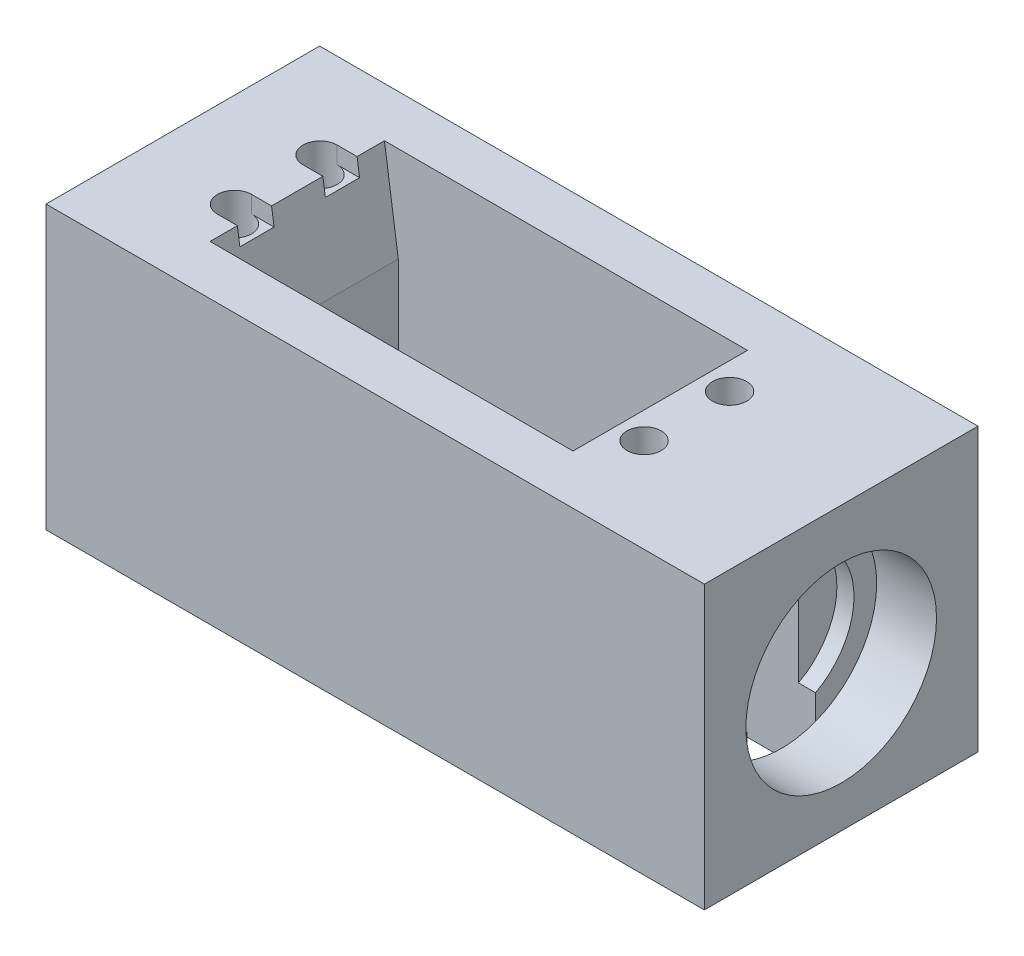
SolidWorks part; units mm, degrees
ref_plane "Front Plane" through (0, 0, 0) normal (0, 0, 1) x (1, 0, 0)
ref_plane "Top Plane" through (0, 0, 0) normal (0, 1, 0) x (1, 0, 0)
ref_plane "Right Plane" through (0, 0, 0) normal (1, 0, 0) x (0, 0, -1)
sketch "Sketch2" plane through (0, 0, 0) normal (0, 1, 0) x (1, 0, 0)
  line L1 (0, 0) -> (40, 0) construction
  line L2 (0, 0) -> (0, 20) construction
  line L3 (0, 20) -> (40, 20) construction
  line L4 (40, 0) -> (40, 20) construction
  line L5 (0, 20) -> (-8, 20)
  line L6 (0, 20) -> (0, 0)
  line L7 (0, 0) -> (-8, 0)
  line L8 (-8, 20) -> (-8, 0)
  line L9 (40, 0) -> (48, 0)
  line L10 (40, 0) -> (40, 20)
  line L11 (40, 20) -> (48, 20)
  line L12 (48, 0) -> (48, 20)
  line L13 (-8, 0) -> (48, 0)
  line L14 (-8, 0) -> (-8, -6)
  line L15 (-8, -6) -> (48, -6)
  line L16 (48, 0) -> (48, -6)
  line L17 (0, 0) -> (40, 0) construction
  line L18 (0, 0) -> (0, 20) construction
  line L19 (0, 20) -> (40, 20) construction
  line L20 (40, 0) -> (40, 20) construction
  line L21 (0, 0) -> (40, 20) construction
  line L22 (0, 20) -> (40, 0) construction
  point P8 (20, 10)
  dimension "D1" = 8
  dimension "D2" = 20
  dimension "D3" = 40
  dimension "D7" = 6
extrude "Boss-Extrude1" add sketch "Sketch2" along normal blind 5
sketch "Sketch6" plane through (0, 0, 0) normal (0, -1, 0) x (1, 0, 0)
  line L0 (40, -10) -> (0, -10) construction
  line L1 (-3.95, -5) -> (43.95, -5) construction
  line L2 (-3.95, -5) -> (-3.95, -15) construction
  line L3 (-3.95, -15) -> (43.95, -15) construction
  line L4 (43.95, -5) -> (43.95, -15) construction
  line L5 (40, 0) -> (40, -20) construction
  line L6 (0, -20) -> (0, 0) construction
  line L7 (20, -10) -> (20, -15) construction
  line L8 (20, -10) -> (20, -5) construction
  circle A0 centre (43.95, -5) radius 2
  circle A1 centre (43.95, -15) radius 2
  circle A2 centre (-3.95, -5) radius 2
  circle A3 centre (-3.95, -15) radius 2
  dimension "D3" = 4
  dimension "D1" = 10
  dimension "D2" = 47.9
extrude "Cut-Extrude3" cut sketch "Sketch6" against normal through all contours A2
sketch "Sketch7" plane through (0, 0, 0) normal (0, -1, 0) x (1, 0, 0)
  line L0 (-8, -20) -> (-8, 6) construction
  line L1 (48, 6) -> (-8, 6)
  line L2 (48, 6) -> (48, 0)
  line L3 (48, 0) -> (-8, 0)
  line L4 (-8, 6) -> (-8, 0)
  line L5 (0, 0) -> (40, 0) construction
extrude "Boss-Extrude2" add sketch "Sketch7" along normal blind 28
sketch "Sketch8" plane through (48, 0, 0) normal (1, 0, 0) x (0, 0, -1)
  line L1 (-6, -28) -> (20, -28)
  line L2 (-6, -28) -> (-6, 5)
  line L3 (-6, 5) -> (20, 5)
  line L4 (20, -28) -> (20, 5)
  line M5 (0, 0) -> (20, 0)
  line M6 (20, 0) -> (20, 5)
  line M7 (20, 5) -> (-6, 5)
  line M8 (-6, 5) -> (-6, -28)
  line M9 (-6, -28) -> (0, -28)
  line M10 (0, -28) -> (0, 0)
sketch "Sketch9" plane through (-8, 0, 0) normal (-1, 0, 0) x (0, 0, 1)
  line L1 (-20, 5) -> (6, 5)
  line L2 (-20, 5) -> (-20, -28)
  line L3 (-20, -28) -> (6, -28)
  line L4 (6, 5) -> (6, -28)
  line M1 (-20, 0) -> (0, 0)
  line M2 (0, 0) -> (0, -28)
  line M3 (0, -28) -> (6, -28)
  line M4 (6, -28) -> (6, 5)
  line M5 (6, 5) -> (-20, 5)
  line M6 (-20, 5) -> (-20, 0)
extrude "Boss-Extrude3" add sketch "Sketch9" along normal blind 2 contours M6 M1 M2 M3 M4 M5 | L2 L3 M2 M1
extrude "Boss-Extrude4" add sketch "Sketch8" along normal blind 2 contours L1 L4 M5 M10 | M10 M5 M6 M7 M8 M9
sketch "Sketch10" plane through (0, 0, 0) normal (0, -1, 0) x (1, 0, 0)
  line L4 (0, 0) -> (-8, 0)
  line L5 (-8, 0) -> (-8, -20)
  line L6 (-8, -20) -> (0, -20)
  line L7 (0, -20) -> (0, 0)
  line L8 (0, 0) -> (-8, 0)
  line L9 (-8, 0) -> (-8, -20)
  line L10 (-8, -20) -> (0, -20)
  line L11 (0, -20) -> (0, 0)
  circle A0 centre (-3.95, -5) radius 2 construction
  circle A1 centre (-3.95, -15) radius 2 construction
  circle A2 centre (-3.95, -5) radius 2
  circle A3 centre (-3.95, -15) radius 2
  dimension "D1" = 0
extrude "Boss-Extrude5" add sketch "Sketch10" along normal up to surface (28 mm away) up to face at (20, -28, -8.5)
sketch "Sketch12" plane through (0, 0, -20) normal (0, 0, -1) x (-1, 0, 0)
  line L0 (1.6175, 5) -> (0, -6.1672)
  line L1 (0, 5) -> (10, 5) construction
  line L2 (0, 5) -> (0, -28) construction
  line L3 (0, -6.1672) -> (0, 5)
  line L4 (0, 5) -> (1.6175, 5)
  line L5 (-40, 2.5) -> (-40.8379, 5)
  line L6 (-40, 5) -> (-50, 5) construction
  line L7 (-40.8379, 5) -> (-40, 5)
  line L8 (-40, 5) -> (-40, 2.5)
  line L9 (-40, 5) -> (-40, 0) construction
  line M1 (0, 5) -> (0, -28)
  line M4 (10, 5) -> (0, 5)
extrude "Cut-Extrude4" cut sketch "Sketch12" against normal up to surface (20 mm away) contours L8 L7 L5 | L0 M4 M1 up to face at (29.3333, -7.6667, 0)
sketch "Sketch13" plane through (0, 5, 0) normal (0, 1, 0) x (1, 0, 0)
  line L0 (0, 0) -> (0, 20) construction
  line L1 (-3.95, 7) -> (0, 7)
  line L2 (-3.95, 7) -> (-3.95, 3)
  line L3 (-3.95, 3) -> (0, 3)
  line L4 (0, 7) -> (0, 3)
  line L5 (-3.95, 17) -> (0, 17)
  line L6 (-3.95, 17) -> (-3.95, 13)
  line L7 (-3.95, 13) -> (0, 13)
  line L8 (0, 17) -> (0, 13)
  circle A0 centre (-3.95, 15) radius 2 construction
  circle A1 centre (-3.95, 5) radius 2 construction
  circle A2 centre (-3.95, 15) radius 2 construction
  circle A3 centre (-3.95, 5) radius 2 construction
extrude "Cut-Extrude5" cut sketch "Sketch13" against normal blind 2
sketch "Sketch14" plane through (0, 0, -20) normal (0, 0, -1) x (-1, 0, 0)
  line L1 (-50, 5) -> (10, 5)
  line L2 (-50, 5) -> (-50, -28)
  line L3 (-50, -28) -> (10, -28)
  line L4 (10, 5) -> (10, -28)
extrude "Boss-Extrude6" add sketch "Sketch14" along normal blind 6
sketch "Sketch15" plane through (0, -28, 0) normal (0, -1, 0) x (1, 0, 0)
  circle A0 centre (-3.95, -5) radius 2 construction
  circle A1 centre (-3.95, -15) radius 2 construction
  circle A2 centre (-3.95, -5) radius 2
  circle A3 centre (-3.95, -15) radius 2
extrude "Boss-Extrude7" add sketch "Sketch15" against normal blind 20
sketch "Sketch16" plane through (50, 0, 0) normal (1, 0, 0) x (0, 0, -1)
  line L4 (-6, -28) -> (26, -28)
  line L5 (26, -28) -> (26, 5)
  line L6 (26, 5) -> (-6, 5)
  line L7 (-6, 5) -> (-6, -28)
  line L8 (-6, -28) -> (26, -28)
  line L9 (26, -28) -> (26, 5)
  line L10 (26, 5) -> (-6, 5)
  line L11 (-6, 5) -> (-6, -28)
  dimension "D1" = 0
extrude "Boss-Extrude8" add sketch "Sketch16" along normal blind 12
sketch "Sketch20" plane through (-10, 0, 0) normal (-1, 0, 0) x (0, 0, 1)
  line L4 (6, 5) -> (-26, 5)
  line L5 (-26, 5) -> (-26, -28)
  line L6 (-26, -28) -> (6, -28)
  line L7 (6, -28) -> (6, 5)
  line L8 (6, 5) -> (-26, 5)
  line L9 (-26, 5) -> (-26, -28)
  line L10 (-26, -28) -> (6, -28)
  line L11 (6, -28) -> (6, 5)
  dimension "D1" = 0
extrude "Boss-Extrude9" add sketch "Sketch20" along normal blind 5
sketch "Sketch17" plane through (62, 0, 0) normal (1, 0, 0) x (0, 0, -1)
  line L0 (10, -28) -> (10, -12) construction
  line L1 (-6, -28) -> (26, -28) construction
  circle A0 centre (10, -12) radius 11.15
  dimension "D1" = 22.3
  dimension "D2" = 16
extrude "Cut-Extrude6" cut sketch "Sketch17" against normal blind 7
sketch "Sketch19" plane through (-15, 0, 0) normal (-1, 0, 0) x (0, 0, 1)
  circle A0 centre (-10, -12) radius 11.15 construction
  circle A1 centre (-10, -12) radius 11.15
extrude "Cut-Extrude7" cut sketch "Sketch19" against normal blind 7
sketch "Sketch21" plane through (55, 0, 0) normal (1, 0, 0) x (0, 0, -1)
  circle A0 centre (10, -12) radius 8.5
  dimension "D1" = 17
extrude "Cut-Extrude8" cut sketch "Sketch21" against normal blind 2
sketch "Sketch22" plane through (0, -28, 0) normal (0, -1, 0) x (1, 0, 0)
  line L0 (48, -10) -> (51.5, -10) construction
  line L1 (48, 0) -> (48, -20) construction
  line L3 (55, -6) -> (48, -6)
  line L4 (55, -6) -> (55, -14)
  line L5 (55, -14) -> (48, -14)
  line L6 (48, -6) -> (48, -14)
  line L7 (55, -6) -> (48, -14) construction
  line L8 (55, -14) -> (48, -6) construction
  dimension "D1" = 8
  dimension "D2" = 7
extrude "Cut-Extrude10" cut sketch "Sketch22" against normal up to surface (28 mm away) contours L5 L6 L3 L4
sketch "Sketch25" plane through (0, 0, 0) normal (0, -1, 0) x (1, 0, 0)
  line L0 (48, -20) -> (48, -14) construction
  line L1 (40, 0) -> (48, 0)
  line L2 (40, 0) -> (40, -6)
  line L3 (40, -6) -> (48, -6)
  line L4 (48, 0) -> (48, -6)
  line L5 (40, -20) -> (48, -20)
  line L6 (40, -20) -> (40, -14)
  line L7 (40, -14) -> (48, -14)
  line L8 (48, -20) -> (48, -14)
  line L9 (48, -6) -> (48, 0) construction
  line L10 (55, -14) -> (48, -14) construction
extrude "Boss-Extrude10" add sketch "Sketch25" along normal up to surface (28 mm away) up to face at (37.75, -28, -10)
sketch "Sketch26" plane through (0, 5, 0) normal (0, 1, 0) x (1, 0, 0)
  circle A0 centre (43.95, 5) radius 2 construction
  circle A1 centre (43.95, 15) radius 2 construction
  circle A2 centre (43.95, 5) radius 2
  circle A3 centre (43.95, 15) radius 2
extrude "Cut-Extrude11" cut sketch "Sketch26" against normal blind 12
sketch "Sketch27" plane through (-8, 0, 0) normal (-1, 0, 0) x (0, 0, 1)
  arc A0 (-6, -19.5) -> (-6, -4.5) centre (-10, -12) ccw construction
  arc A1 (-14, -4.5) -> (-14, -19.5) centre (-10, -12) ccw construction
  arc A2 (-6, -19.5) -> (-6, -4.5) centre (-10, -12) ccw construction
  arc A3 (-14, -4.5) -> (-14, -19.5) centre (-10, -12) ccw construction
  circle A4 centre (-10, -12) radius 8.5
extrude "Cut-Extrude12" cut sketch "Sketch27" against normal blind 2
sketch "Sketch28" plane through (0, 0, 0) normal (0, 0, -1) x (-1, 0, 0)
  line L6 (-40, 2.5) -> (-40, -28)
  line L7 (-40, -28) -> (0, -28)
  line L8 (0, -28) -> (0, -6.1672)
  line L9 (0, -6.1672) -> (1.6175, 5)
  line L10 (1.6175, 5) -> (-40.8379, 5)
  line L11 (-40.8379, 5) -> (-40, 2.5)
  line L12 (-40, 2.5) -> (-40, -28)
  line L13 (-40, -28) -> (0, -28)
  line L14 (0, -28) -> (0, -6.1672)
  line L15 (0, -6.1672) -> (1.6175, 5)
  line L16 (1.6175, 5) -> (-40.8379, 5)
  line L17 (-40.8379, 5) -> (-40, 2.5)
  dimension "D1" = 0
extrude "Cut-Extrude13" cut sketch "Sketch28" against normal blind 0.2
sketch "Sketch29" plane through (0, 0, -20) normal (0, 0, 1) x (1, 0, 0)
  line L6 (0, -28) -> (40, -28)
  line L7 (40, -28) -> (40, 2.5)
  line L8 (40, 2.5) -> (40.8379, 5)
  line L9 (40.8379, 5) -> (-1.6175, 5)
  line L10 (-1.6175, 5) -> (0, -6.1672)
  line L11 (0, -6.1672) -> (0, -28)
  line L12 (0, -28) -> (40, -28)
  line L13 (40, -28) -> (40, 2.5)
  line L14 (40, 2.5) -> (40.8379, 5)
  line L15 (40.8379, 5) -> (-1.6175, 5)
  line L16 (-1.6175, 5) -> (0, -6.1672)
  line L17 (0, -6.1672) -> (0, -28)
  dimension "D1" = 0
extrude "Cut-Extrude14" cut sketch "Sketch29" against normal blind 0.2
